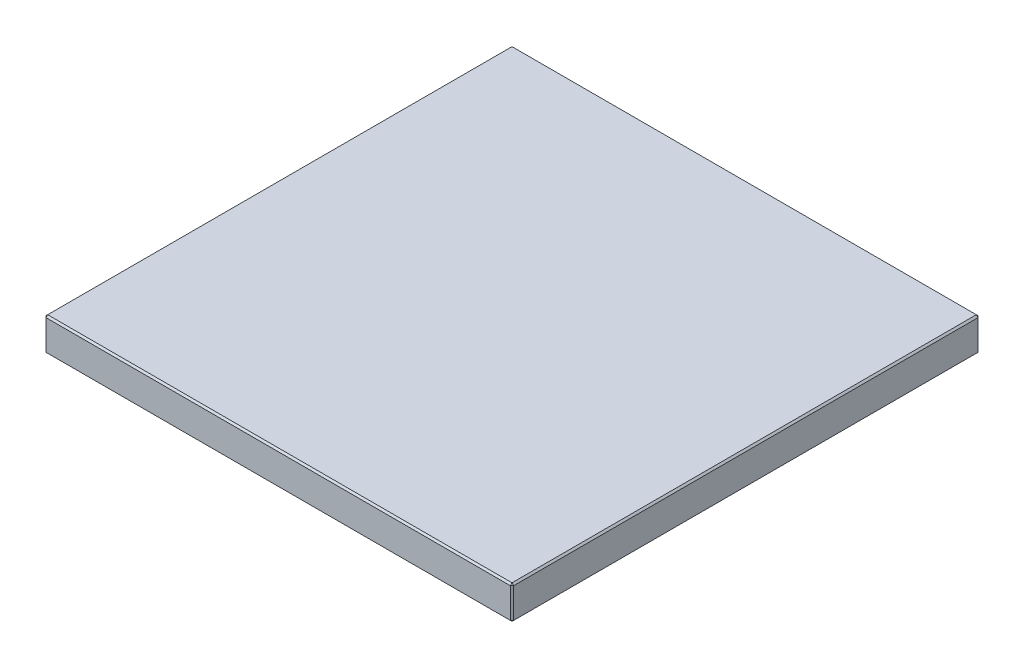
SolidWorks part; units mm, degrees
ref_plane "Front Plane" through (0, 0, 0) normal (0, 0, 1) x (1, 0, 0)
ref_plane "Top Plane" through (0, 0, 0) normal (0, 1, 0) x (1, 0, 0)
ref_plane "Right Plane" through (0, 0, 0) normal (1, 0, 0) x (0, 0, -1)
sketch "Sketch1" plane through (0, 0, 0) normal (0, 0, 1) x (1, 0, 0)
  line L0 (-44.45, 0) -> (44.45, 0) construction
  line L1 (0, 3.175) -> (0, -3.175) construction
  point P4 (0, 0)
  point P8 (0, 0)
  dimension "Width" = 88.9
  dimension "Thickness" = 6.35
sketch "Sketch2" plane through (0, 0, 0) normal (1, 0, 0) x (0, 0, -1)
  line L0 (44.45, 0) -> (-44.45, 0) construction
  point P4 (0, 0)
  dimension "Length" = 88.9
sketch "Sketch3" plane through (0, 0, 0) normal (0, 0, 1) x (1, 0, 0)
  line L1 (-44.45, -3.175) -> (44.45, -3.175)
  line L2 (-44.45, -3.175) -> (-44.45, 3.175)
  line L3 (-44.45, 3.175) -> (44.45, 3.175)
  line L4 (44.45, -3.175) -> (44.45, 3.175)
  line L5 (-44.45, -3.175) -> (44.45, 3.175) construction
  line L6 (-44.45, 3.175) -> (44.45, -3.175) construction
  point P0 (0, 0)
  point P6 (0, 3.175)
  point P8 (44.45, 0)
extrude "Boss-Extrude1" add sketch "Sketch3" along normal mid plane 88.9
sketch "Sketch4" plane through (0, 3.175, 0) normal (0, 1, 0) x (1, 0, 0)
  line L4 (44.45, 44.45) -> (-44.45, 44.45)
  line L5 (-44.45, 44.45) -> (-44.45, -44.45)
  line L6 (-44.45, -44.45) -> (44.45, -44.45)
  line L7 (44.45, -44.45) -> (44.45, 44.45)
  line L8 (44.45, 44.45) -> (-44.45, 44.45)
  line L9 (-44.45, 44.45) -> (-44.45, -44.45)
  line L10 (-44.45, -44.45) -> (44.45, -44.45)
  line L11 (44.45, -44.45) -> (44.45, 44.45)
  dimension "D2" = 88.9
  dimension "D3" = 88.9
  dimension "D1" = 0
sketch "Sketch5" plane through (44.45, 0, 0) normal (1, 0, 0) x (0, 0, -1)
  line L4 (44.45, -3.175) -> (44.45, 3.175)
  line L5 (44.45, 3.175) -> (-44.45, 3.175)
  line L6 (-44.45, 3.175) -> (-44.45, -3.175)
  line L7 (-44.45, -3.175) -> (44.45, -3.175)
  line L8 (44.45, -3.175) -> (44.45, 3.175)
  line L9 (44.45, 3.175) -> (-44.45, 3.175)
  line L10 (-44.45, 3.175) -> (-44.45, -3.175)
  line L11 (-44.45, -3.175) -> (44.45, -3.175)
  dimension "D2" = 6.35
  dimension "D1" = 0
chamfer "Chamfer1" distance 0.3175 angle 45 12 edges at (-44.45, 0, 44.45) (-44.45, -3.175, 0) (44.45, -3.175, 0) (0, -3.175, 44.45) (0, -3.175, -44.45) (-44.45, 0, -44.45) (44.45, 0, -44.45) (0, 3.175, -44.45) (-44.45, 3.175, 0) (44.45, 0, 44.45) (44.45, 3.175, 0) (0, 3.175, 44.45)
equation "\"D1@Boss-Extrude1\"=\"Length@Sketch2\""
